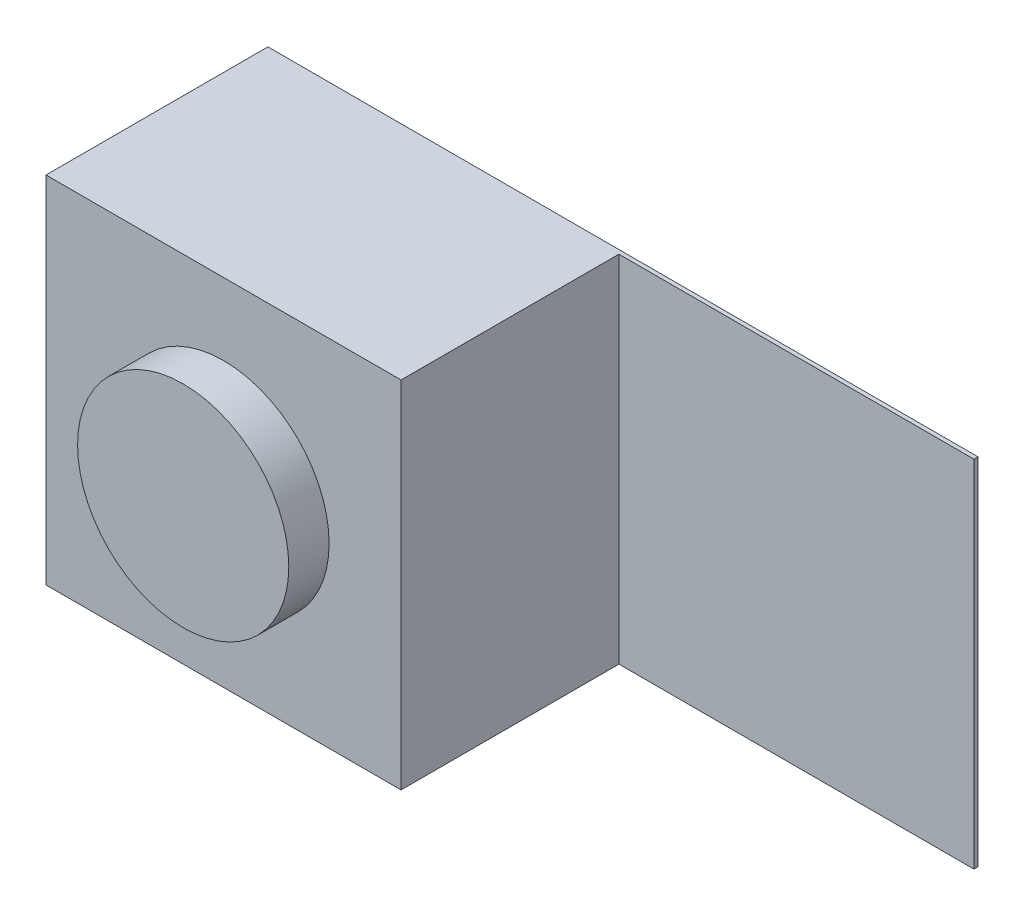
SolidWorks part; units mm, degrees
ref_plane "Front Plane" through (0, 0, 0) normal (0, 0, 1) x (1, 0, 0)
ref_plane "Top Plane" through (0, 0, 0) normal (0, 1, 0) x (1, 0, 0)
ref_plane "Right Plane" through (0, 0, 0) normal (1, 0, 0) x (0, 0, -1)
sketch "Sketch1" plane through (0, 0, 0) normal (0, 0, 1) x (1, 0, 0)
  line L1 (-4.4, 4.4) -> (4.4, 4.4)
  line L2 (-4.4, 4.4) -> (-4.4, -4.4)
  line L3 (-4.4, -4.4) -> (4.4, -4.4)
  line L4 (4.4, 4.4) -> (4.4, -4.4)
  line L5 (-4.4, 4.4) -> (4.4, -4.4) construction
  line L6 (-4.4, -4.4) -> (4.4, 4.4) construction
  point P0 (0, 0)
  dimension "D1" = 8.8
  dimension "D2" = 8.8
extrude "Boss-Extrude1" add sketch "Sketch1" along normal blind 5.5
sketch "Sketch2" plane through (0, 0, 0) normal (0, 0, -1) x (-1, 0, 0)
  line L0 (-4.4, -4.4) -> (-4.4, 4.4) construction
  line L1 (-13.2, -4.4) -> (4.4, -4.4)
  line L2 (-13.2, -4.4) -> (-13.2, 4.4)
  line L3 (-13.2, 4.4) -> (4.4, 4.4)
  line L4 (4.4, -4.4) -> (4.4, 4.4)
  line L5 (-13.2, -4.4) -> (4.4, 4.4) construction
  line L6 (-13.2, 4.4) -> (4.4, -4.4) construction
  point P0 (-4.4, 0)
extrude "Boss-Extrude2" add sketch "Sketch2" against normal blind 0.1
sketch "Sketch3" plane through (0, 0, 5.5) normal (0, 0, 1) x (1, 0, 0)
  circle A0 centre (0, 0) radius 2.6174
extrude "Boss-Extrude3" add sketch "Sketch3" along normal blind 1
